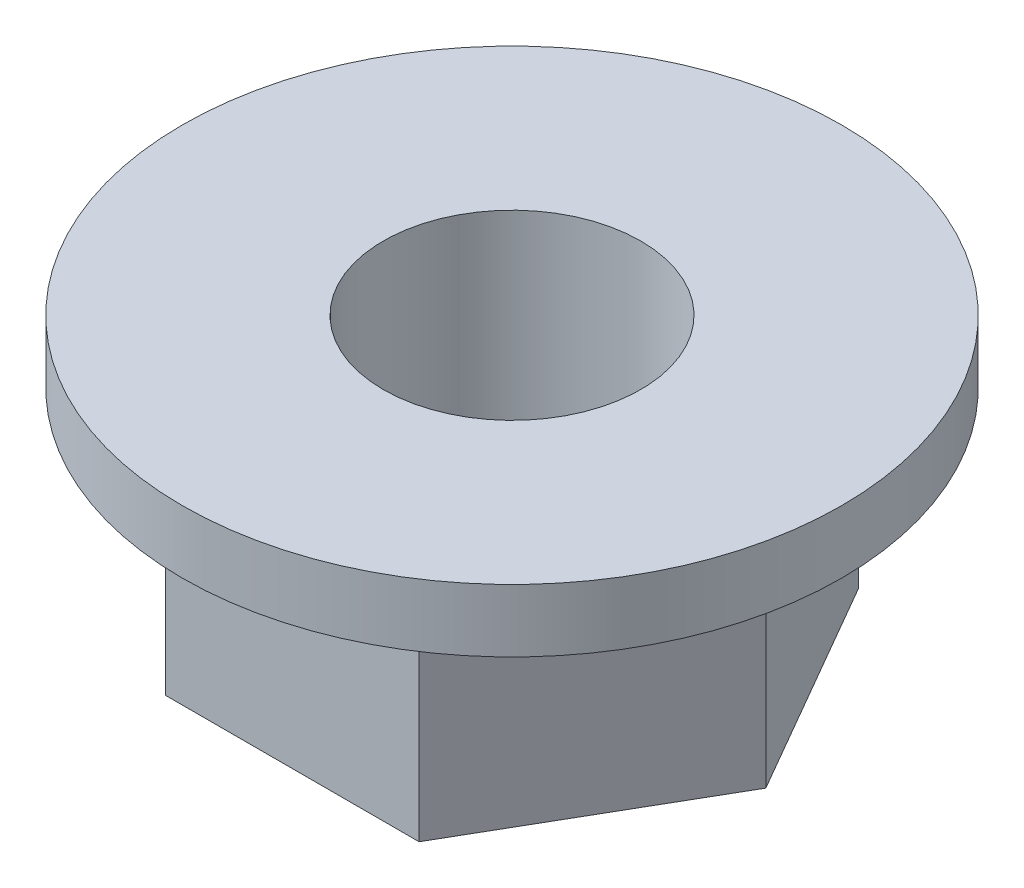
SolidWorks part; units mm, degrees
ref_plane "Front Plane" through (0, 0, 0) normal (0, 0, 1) x (1, 0, 0)
ref_plane "Top Plane" through (0, 0, 0) normal (0, 1, 0) x (1, 0, 0)
ref_plane "Right Plane" through (0, 0, 0) normal (1, 0, 0) x (0, 0, -1)
sketch3d "Hex Nut Sketch datum points"
  point P0 (0, -138.5, 0)
  point P1 (10, -138.5, 0)
  point P2 (0, -138.5, -10)
ref_plane "Hex Nut Sketch plane" through (0, -138.5, 0) normal (0, 1, 0) x (1, 0, 0)
sketch "Hex Nut Sketch" plane through (0, -138.5, 0) normal (0, 1, 0) x (1, 0, 0)
  line L0 (-16.2502, 0) -> (-18.2709, -3.5)
  line L1 (-18.2709, -3.5) -> (-22.3124, -3.5)
  line L2 (-22.3124, -3.5) -> (-24.3331, 0)
  line L3 (-24.3331, 0) -> (-22.3124, 3.5)
  line L4 (-22.3124, 3.5) -> (-18.2709, 3.5)
  line L5 (-18.2709, 3.5) -> (-16.2502, 0)
extrude "Hex Nut" add sketch "Hex Nut Sketch" along normal blind 3.5 separate body
sketch3d "Nut Flange Sketch datum points"
  point P0 (0, -135, 0)
  point P1 (10, -135, 0)
  point P2 (0, -135, -10)
ref_plane "Nut Flange Sketch plane" through (0, -135, 0) normal (0, 1, 0) x (1, 0, 0)
sketch "Nut Flange Sketch" plane through (0, -135, 0) normal (0, 1, 0) x (1, 0, 0)
  circle A0 centre (-20.2917, 0) radius 5.25
extrude "Nut Flange" add sketch "Nut Flange Sketch" along normal blind 1
sketch3d "M4 Internal Thread Blank Sketch datum points"
  point P0 (0, -138.6, 0)
  point P1 (10, -138.6, 0)
  point P2 (0, -138.6, -10)
ref_plane "M4 Internal Thread Blank Sketch plane" through (0, -138.6, 0) normal (0, 1, 0) x (1, 0, 0)
sketch "M4 Internal Thread Blank Sketch" plane through (0, -138.6, 0) normal (0, 1, 0) x (1, 0, 0)
  circle A0 centre (-20.2917, 0) radius 2.05
extrude "M4 Internal Thread Blank" cut sketch "M4 Internal Thread Blank Sketch" along normal blind 4.7
